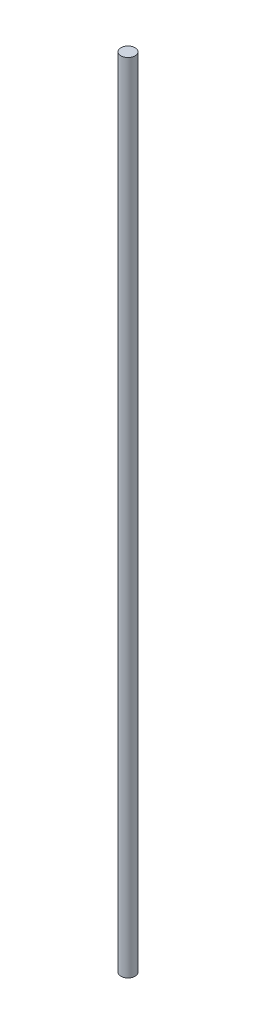
SolidWorks part; units mm, degrees
ref_plane "Front Plane" through (0, 0, 0) normal (0, 0, 1) x (1, 0, 0)
ref_plane "Top Plane" through (0, 0, 0) normal (0, 1, 0) x (1, 0, 0)
ref_plane "Right Plane" through (0, 0, 0) normal (1, 0, 0) x (0, 0, -1)
ref_plane "Plane1"
sketch "Sketch1" plane through (0, 0, 0) normal (0, 1, 0) x (-1, 0, 0)
  circle A0 centre (0, 0) radius 3.15
  dimension "D1" = 6.3
extrude "Extrusion1" add sketch "Sketch1" along normal blind 355.6
